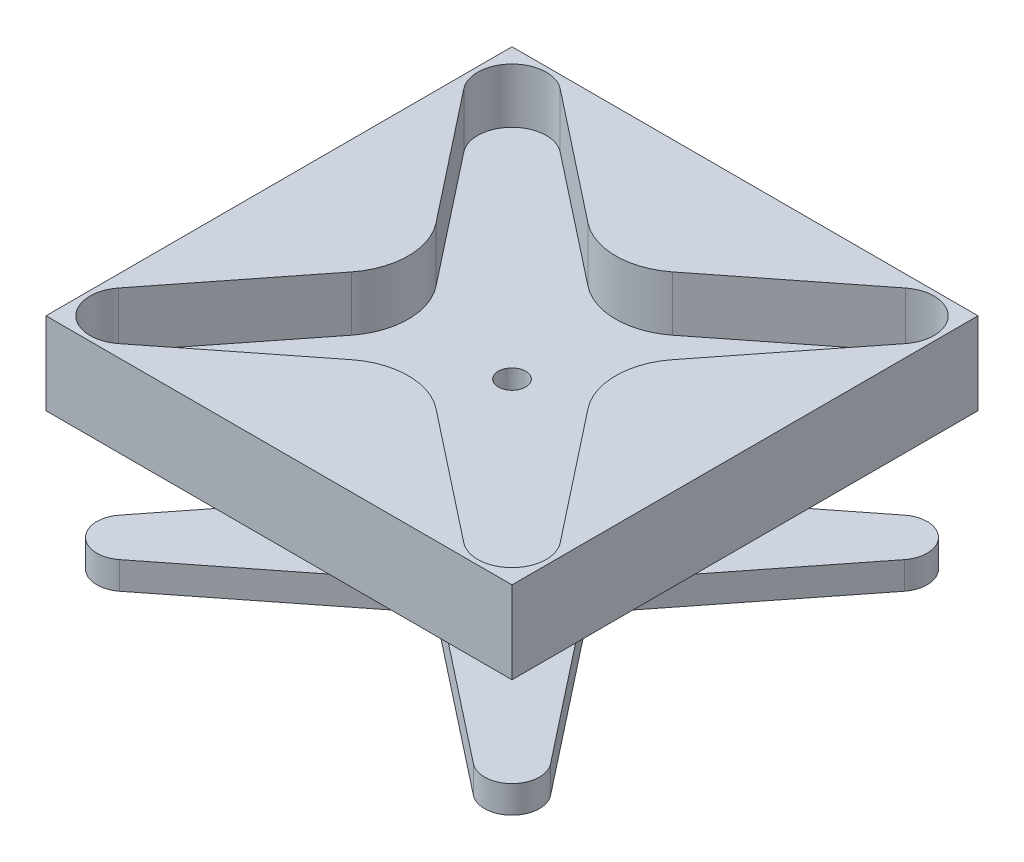
SolidWorks part; units mm, degrees
ref_plane "Front Plane" through (0, 0, 0) normal (0, 0, 1) x (1, 0, 0)
ref_plane "Top Plane" through (0, 0, 0) normal (0, 1, 0) x (1, 0, 0)
ref_plane "Right Plane" through (0, 0, 0) normal (1, 0, 0) x (0, 0, -1)
sketch "Sketch1" plane through (0, 0, 0) normal (0, 1, 0) x (1, 0, 0)
  line L0 (-23.4053, 23.4053) -> (19.0732, -19.0732) construction
  line L1 (21.6874, 21.6874) -> (-15.8004, -15.8004) construction
  line L2 (0, 0) -> (31.3801, 0) construction
  line L3 (0, 5.5682) -> (12.9035, 15.717)
  line L4 (15.717, 12.9035) -> (5.5682, 0)
  line L5 (5.5682, 0) -> (15.717, -12.9035)
  line L6 (12.9035, -15.717) -> (0, -5.5682)
  line L7 (0, -5.5682) -> (-12.9035, -15.717)
  line L8 (-15.717, -12.9035) -> (-5.5682, 0)
  line L9 (-5.5682, 0) -> (-15.717, 12.9035)
  line L10 (-12.9035, 15.717) -> (0, 5.5682)
  arc A1 (15.717, 12.9035) -> (12.9035, 15.717) centre (14.1421, 14.1421) ccw
  arc A2 (12.9035, -15.717) -> (15.717, -12.9035) centre (14.1421, -14.1421) ccw
  arc A3 (-15.717, -12.9035) -> (-12.9035, -15.717) centre (-14.1421, -14.1421) ccw
  arc A4 (-12.9035, 15.717) -> (-15.717, 12.9035) centre (-14.1421, 14.1421) ccw
  point P59 (0, 0)
  point P93 (-0.01, 0.035)
  dimension "D1" = 45
  dimension "D2" = 2.0036
  dimension "D3" = 20
  dimension "D7" = 4
extrude "Boss-Extrude2" add sketch "Sketch1" along normal blind 2
ref_plane "Plane1" through (0, 10, 0) normal (0, 1, 0) x (1, 0, 0)
sketch "Sketch2" plane through (0, 10, 0) normal (0, 1, 0) x (1, 0, 0)
  line L1 (17, -17) -> (-17, -17)
  line L2 (17, -17) -> (17, 17)
  line L3 (17, 17) -> (-17, 17)
  line L4 (-17, -17) -> (-17, 17)
  line L5 (17, -17) -> (-17, 17) construction
  line L6 (17, 17) -> (-17, -17) construction
  point P1 (0, 0)
  dimension "D1" = 34
  dimension "D2" = 34
extrude "Boss-Extrude3" add sketch "Sketch2" along normal blind 6 separate body
sketch "Sketch3" plane through (0, 16, 0) normal (0, 1, 0) x (1, 0, 0)
  line L0 (-16.11, 12.5944) -> (-6.2043, 0)
  line L1 (-6.2043, 0) -> (-16.11, -12.5944)
  line L2 (-12.5944, -16.11) -> (0, -6.2043)
  line L3 (0, -6.2043) -> (12.5944, -16.11)
  line L4 (16.11, -12.5944) -> (6.2043, 0)
  line L5 (6.2043, 0) -> (16.11, 12.5944)
  line L6 (12.5944, 16.11) -> (0, 6.2043)
  line L7 (0, 6.2043) -> (-12.5944, 16.11)
  line L8 (-15.717, 12.9035) -> (-5.5682, 0)
  line L9 (0, 5.5682) -> (-12.9035, 15.717)
  line L10 (12.9035, 15.717) -> (0, 5.5682)
  line L11 (5.5682, 0) -> (15.717, 12.9035)
  line L12 (15.717, -12.9035) -> (5.5682, 0)
  line L13 (0, -5.5682) -> (12.9035, -15.717)
  line L14 (-12.9035, -15.717) -> (0, -5.5682)
  line L15 (-5.5682, 0) -> (-15.717, -12.9035)
  line L16 (-15.717, 12.9035) -> (-5.5682, 0)
  line L17 (0, 5.5682) -> (-12.9035, 15.717)
  line L18 (12.9035, 15.717) -> (0, 5.5682)
  line L19 (5.5682, 0) -> (15.717, 12.9035)
  line L20 (15.717, -12.9035) -> (5.5682, 0)
  line L21 (0, -5.5682) -> (12.9035, -15.717)
  line L22 (-12.9035, -15.717) -> (0, -5.5682)
  line L23 (-5.5682, 0) -> (-15.717, -12.9035)
  arc A0 (-16.11, -12.5944) -> (-12.5944, -16.11) centre (-14.1421, -14.1421) ccw
  arc A1 (12.5944, -16.11) -> (16.11, -12.5944) centre (14.1421, -14.1421) ccw
  arc A2 (16.11, 12.5944) -> (12.5944, 16.11) centre (14.1421, 14.1421) ccw
  arc A3 (-12.5944, 16.11) -> (-16.11, 12.5944) centre (-14.1421, 14.1421) ccw
  arc A4 (-12.9035, 15.717) -> (-15.717, 12.9035) centre (-14.1421, 14.1421) ccw
  arc A5 (15.717, 12.9035) -> (12.9035, 15.717) centre (14.1421, 14.1421) ccw
  arc A6 (12.9035, -15.717) -> (15.717, -12.9035) centre (14.1421, -14.1421) ccw
  arc A7 (-15.717, -12.9035) -> (-12.9035, -15.717) centre (-14.1421, -14.1421) ccw
  arc A8 (-12.9035, 15.717) -> (-15.717, 12.9035) centre (-14.1421, 14.1421) ccw
  arc A9 (15.717, 12.9035) -> (12.9035, 15.717) centre (14.1421, 14.1421) ccw
  arc A10 (12.9035, -15.717) -> (15.717, -12.9035) centre (14.1421, -14.1421) ccw
  arc A11 (-15.717, -12.9035) -> (-12.9035, -15.717) centre (-14.1421, -14.1421) ccw
  dimension "D1" = 0
  dimension "D2" = 0.5
extrude "Cut-Extrude1" cut sketch "Sketch3" against normal blind 4 contours L23 A11 L22 L21 A10 L20 L19 A9 L18 L17 A8 L16 | L7 A3 L0 L1 A0 L2 L3 A1 L4 L5 A2 L6 A11 L23 L16 A8 L17 L18 A9 L19 L20 A10 L21 L22
fillet "Fillet1" radius 5 4 edges at (0, 14, 6.2043) (6.2043, 14, 0) (-6.2043, 14, 0) (0, 14, -6.2043)
sketch "Sketch4" plane through (0, 12, 0) normal (0, 1, 0) x (1, 0, 0)
  circle A0 centre (0, 0) radius 1
  dimension "D1" = 2
extrude "Cut-Extrude2" cut sketch "Sketch4" against normal blind 10
